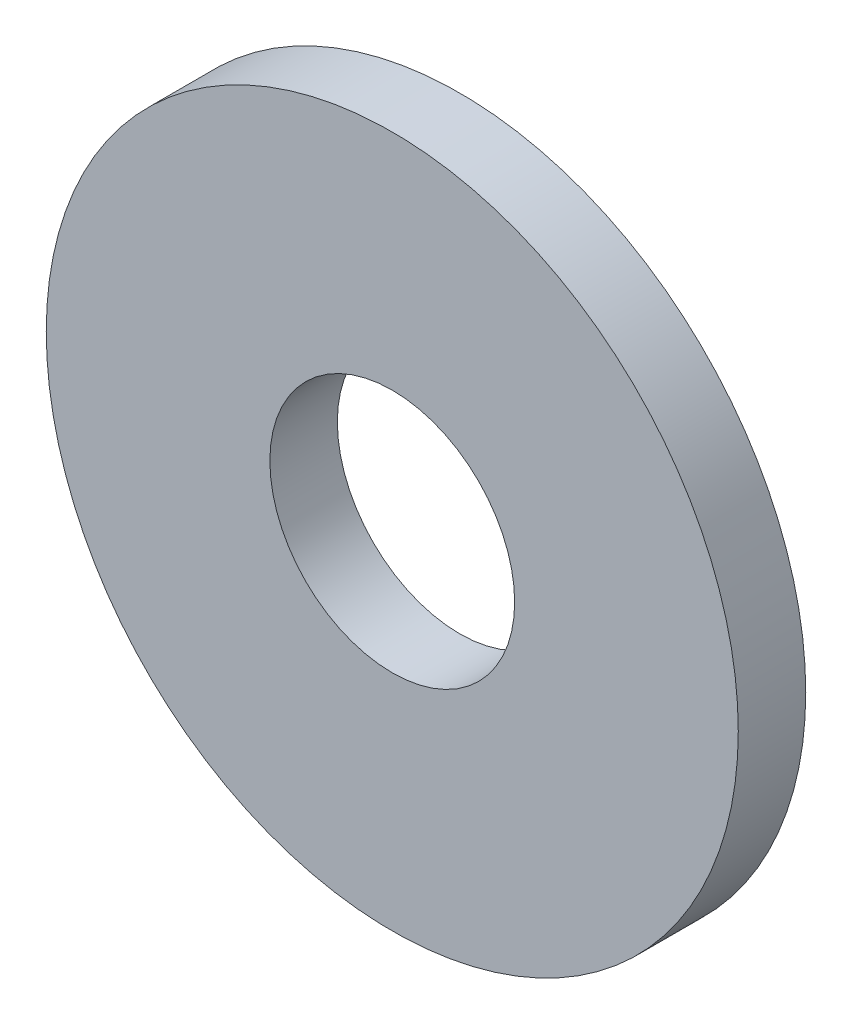
SolidWorks part; units mm, degrees
ref_plane "Front Plane" through (0, 0, 0) normal (0, 0, 1) x (1, 0, 0)
ref_plane "Top Plane" through (0, 0, 0) normal (0, 1, 0) x (1, 0, 0)
ref_plane "Right Plane" through (0, 0, 0) normal (1, 0, 0) x (0, 0, -1)
sketch "Sketch1" plane through (0, 0, 0) normal (0, 0, 1) x (1, 0, 0)
  circle A0 centre (0, 0) radius 4.41
  circle A1 centre (0, 0) radius 1.56
  dimension "D1" = 8.82
extrude "Boss-Extrude1" add sketch "Sketch1" along normal blind 0.86
